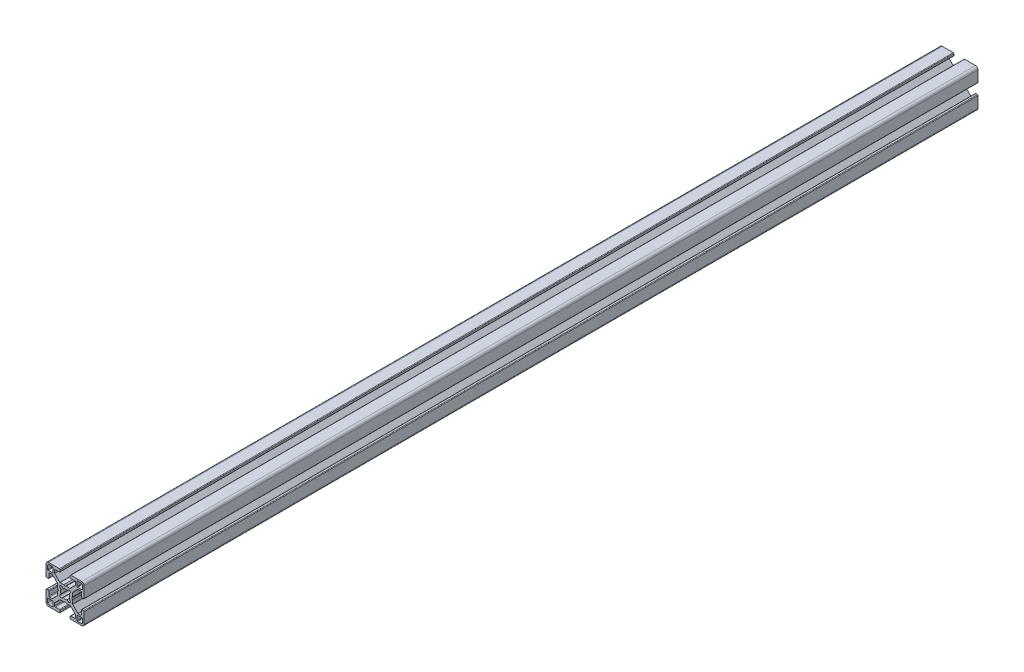
SolidWorks part; units mm, degrees
material "6105-T5 Aluminum"
ref_plane "Front Plane" through (0, 0, 0) normal (0, 0, 1) x (1, 0, 0)
ref_plane "Top Plane" through (0, 0, 0) normal (0, 1, 0) x (1, 0, 0)
ref_plane "Right Plane" through (0, 0, 0) normal (1, 0, 0) x (0, 0, -1)
sketch "Sketch1" plane through (0, 0, 0) normal (0, 0, 1) x (1, 0, 0)
  line L0 (9.5, -13.3189) -> (9.5, -9.88)
  line L1 (9.88, -9.5) -> (13.3189, -9.5)
  line L2 (13.6999, -9.881) -> (13.6999, -12.6999)
  line L3 (12.6999, -13.6999) -> (9.881, -13.6999)
  line L4 (-13.3189, -9.5) -> (-9.88, -9.5)
  line L5 (-9.5, -9.88) -> (-9.5, -13.3189)
  line L6 (-9.881, -13.6999) -> (-12.6999, -13.6999)
  line L7 (-13.6999, -12.6999) -> (-13.6999, -9.881)
  line L8 (-1.4942, -3.1981) -> (-2.4733, -3.9799)
  line L9 (-3.9799, -2.4733) -> (-3.1981, -1.4942)
  line L10 (-3.1981, 1.4942) -> (-3.9799, 2.4733)
  line L11 (-2.4733, 3.9799) -> (-1.4942, 3.1981)
  line L12 (1.4942, 3.1981) -> (2.4733, 3.9799)
  line L13 (3.9799, 2.4733) -> (3.1981, 1.4942)
  line L14 (3.1981, -1.4942) -> (3.9799, -2.4733)
  line L15 (2.4733, -3.9799) -> (1.4942, -3.1981)
  line L16 (-9.5, 13.3189) -> (-9.5, 9.88)
  line L17 (-9.88, 9.5) -> (-13.3189, 9.5)
  line L18 (-13.6999, 9.881) -> (-13.6999, 12.6999)
  line L19 (-12.6999, 13.6999) -> (-9.881, 13.6999)
  line L20 (9.881, 13.6999) -> (12.6999, 13.6999)
  line L21 (13.6999, 12.6999) -> (13.6999, 9.881)
  line L22 (13.3189, 9.5) -> (9.88, 9.5)
  line L23 (9.5, 9.88) -> (9.5, 13.3189)
  line L24 (12.7425, -4.5) -> (12.7425, -7.7325)
  line L25 (12.2428, -8.25) -> (10.2602, -8.25)
  line L26 (9.9066, -8.1035) -> (5.9811, -4.178)
  line L27 (5.8347, -3.8245) -> (5.8347, -1.0125)
  line L28 (5.8347, -1.0125) -> (5.3247, -0.0625)
  line L29 (5.3247, -0.0625) -> (5.8347, 0.8875)
  line L30 (5.8347, 0.8875) -> (5.8347, 3.8245)
  line L31 (5.9811, 4.178) -> (9.9066, 8.1035)
  line L32 (10.2602, 8.25) -> (12.2428, 8.25)
  line L33 (12.7425, 7.7325) -> (12.7425, 4.5)
  line L34 (13.2425, 4) -> (14.4999, 4)
  line L35 (14.9999, 4.5) -> (14.9999, 12.9999)
  line L36 (12.9999, 14.9999) -> (4.5, 14.9999)
  line L37 (4, 14.4999) -> (4, 13.2425)
  line L38 (4.5, 12.7425) -> (7.7325, 12.7425)
  line L39 (8.25, 12.2428) -> (8.25, 10.2602)
  line L40 (8.1035, 9.9066) -> (4.178, 5.9811)
  line L41 (3.8245, 5.8347) -> (0.95, 5.8347)
  line L42 (0.95, 5.8347) -> (0, 5.3247)
  line L43 (0, 5.3247) -> (-0.95, 5.8347)
  line L44 (-0.95, 5.8347) -> (-3.8245, 5.8347)
  line L45 (-4.178, 5.9811) -> (-8.1035, 9.9066)
  line L46 (-8.25, 10.2602) -> (-8.25, 12.2428)
  line L47 (-7.7325, 12.7425) -> (-4.5, 12.7425)
  line L48 (-4, 13.2425) -> (-4, 14.4999)
  line L49 (-4.5, 14.9999) -> (-12.9999, 14.9999)
  line L50 (-14.9999, 12.9999) -> (-14.9999, 4.5)
  line L51 (-14.4999, 4) -> (-13.2425, 4)
  line L52 (-12.7425, 4.5) -> (-12.7425, 7.7325)
  line L53 (-12.2428, 8.25) -> (-10.2602, 8.25)
  line L54 (-9.9066, 8.1035) -> (-5.9811, 4.178)
  line L55 (-5.8347, 3.8245) -> (-5.8347, 0.8875)
  line L56 (-5.8347, 0.8875) -> (-5.3247, -0.0625)
  line L57 (-5.3247, -0.0625) -> (-5.8347, -1.0125)
  line L58 (-5.8347, -1.0125) -> (-5.8347, -3.8245)
  line L59 (-5.9811, -4.178) -> (-9.9066, -8.1035)
  line L60 (-10.2602, -8.25) -> (-12.2428, -8.25)
  line L61 (-12.7425, -7.7325) -> (-12.7425, -4.5)
  line L62 (-13.2425, -4) -> (-14.4999, -4)
  line L63 (-14.9999, -4.5) -> (-14.9999, -12.9999)
  line L64 (-12.9999, -14.9999) -> (-4.5, -14.9999)
  line L65 (-4, -14.4999) -> (-4, -13.2425)
  line L66 (-4.5, -12.7425) -> (-7.7325, -12.7425)
  line L67 (-8.25, -12.2428) -> (-8.25, -10.2602)
  line L68 (-8.1035, -9.9066) -> (-4.178, -5.9811)
  line L69 (-3.8245, -5.8347) -> (-0.95, -5.8347)
  line L70 (-0.95, -5.8347) -> (0, -5.3247)
  line L71 (0, -5.3247) -> (0.95, -5.8347)
  line L72 (0.95, -5.8347) -> (3.8245, -5.8347)
  line L73 (4.178, -5.9811) -> (8.1035, -9.9066)
  line L74 (8.25, -10.2602) -> (8.25, -12.2428)
  line L75 (7.7325, -12.7425) -> (4.5, -12.7425)
  line L76 (4, -13.2425) -> (4, -14.4999)
  line L77 (4.5, -14.9999) -> (12.9999, -14.9999)
  line L78 (14.9999, -12.9999) -> (14.9999, -4.5)
  line L79 (14.4999, -4) -> (13.2425, -4)
  arc A0 (9.5, -13.3189) -> (9.881, -13.6999) centre (9.881, -13.3189) ccw
  arc A1 (9.88, -9.5) -> (9.5, -9.88) centre (9.88, -9.88) ccw
  arc A2 (13.6999, -9.881) -> (13.3189, -9.5) centre (13.3189, -9.881) ccw
  arc A3 (12.6999, -13.6999) -> (13.6999, -12.6999) centre (12.6999, -12.6999) ccw
  arc A4 (-13.3189, -9.5) -> (-13.6999, -9.881) centre (-13.3189, -9.881) ccw
  arc A5 (-9.5, -9.88) -> (-9.88, -9.5) centre (-9.88, -9.88) ccw
  arc A6 (-9.881, -13.6999) -> (-9.5, -13.3189) centre (-9.881, -13.3189) ccw
  arc A7 (-13.6999, -12.6999) -> (-12.6999, -13.6999) centre (-12.6999, -12.6999) ccw
  arc A8 (-1.4942, -3.1981) -> (1.4942, -3.1981) centre (0, 0) ccw
  arc A9 (-3.9799, -2.4733) -> (-2.4733, -3.9799) centre (-3.1422, -3.1422) ccw
  arc A10 (-3.1981, 1.4942) -> (-3.1981, -1.4942) centre (0, 0) ccw
  arc A11 (-2.4733, 3.9799) -> (-3.9799, 2.4733) centre (-3.1422, 3.1422) ccw
  arc A12 (1.4942, 3.1981) -> (-1.4942, 3.1981) centre (0, 0) ccw
  arc A13 (3.9799, 2.4733) -> (2.4733, 3.9799) centre (3.1422, 3.1422) ccw
  arc A14 (3.1981, -1.4942) -> (3.1981, 1.4942) centre (0, 0) ccw
  arc A15 (2.4733, -3.9799) -> (3.9799, -2.4733) centre (3.1422, -3.1422) ccw
  arc A16 (-9.5, 13.3189) -> (-9.881, 13.6999) centre (-9.881, 13.3189) ccw
  arc A17 (-9.88, 9.5) -> (-9.5, 9.88) centre (-9.88, 9.88) ccw
  arc A18 (-13.6999, 9.881) -> (-13.3189, 9.5) centre (-13.3189, 9.881) ccw
  arc A19 (-12.6999, 13.6999) -> (-13.6999, 12.6999) centre (-12.6999, 12.6999) ccw
  arc A20 (9.881, 13.6999) -> (9.5, 13.3189) centre (9.881, 13.3189) ccw
  arc A21 (13.6999, 12.6999) -> (12.6999, 13.6999) centre (12.6999, 12.6999) ccw
  arc A22 (13.3189, 9.5) -> (13.6999, 9.881) centre (13.3189, 9.881) ccw
  arc A23 (9.5, 9.88) -> (9.88, 9.5) centre (9.88, 9.88) ccw
  arc A24 (13.2425, -4) -> (12.7425, -4.5) centre (13.2425, -4.5) ccw
  arc A25 (12.2428, -8.25) -> (12.7425, -7.7325) centre (12.2428, -7.75) ccw
  arc A26 (9.9066, -8.1035) -> (10.2602, -8.25) centre (10.2602, -7.75) ccw
  arc A27 (5.8347, -3.8245) -> (5.9811, -4.178) centre (6.3347, -3.8245) ccw
  arc A28 (5.9811, 4.178) -> (5.8347, 3.8245) centre (6.3347, 3.8245) ccw
  arc A29 (10.2602, 8.25) -> (9.9066, 8.1035) centre (10.2602, 7.75) ccw
  arc A30 (12.7425, 7.7325) -> (12.2428, 8.25) centre (12.2428, 7.75) ccw
  arc A31 (12.7425, 4.5) -> (13.2425, 4) centre (13.2425, 4.5) ccw
  arc A32 (14.4999, 4) -> (14.9999, 4.5) centre (14.4999, 4.5) ccw
  arc A33 (14.9999, 12.9999) -> (12.9999, 14.9999) centre (12.9999, 12.9999) ccw
  arc A34 (4.5, 14.9999) -> (4, 14.4999) centre (4.5, 14.4999) ccw
  arc A35 (4, 13.2425) -> (4.5, 12.7425) centre (4.5, 13.2425) ccw
  arc A36 (8.25, 12.2428) -> (7.7325, 12.7425) centre (7.75, 12.2428) ccw
  arc A37 (8.1035, 9.9066) -> (8.25, 10.2602) centre (7.75, 10.2602) ccw
  arc A38 (3.8245, 5.8347) -> (4.178, 5.9811) centre (3.8245, 6.3347) ccw
  arc A39 (-4.178, 5.9811) -> (-3.8245, 5.8347) centre (-3.8245, 6.3347) ccw
  arc A40 (-8.25, 10.2602) -> (-8.1035, 9.9066) centre (-7.75, 10.2602) ccw
  arc A41 (-7.7325, 12.7425) -> (-8.25, 12.2428) centre (-7.75, 12.2428) ccw
  arc A42 (-4.5, 12.7425) -> (-4, 13.2425) centre (-4.5, 13.2425) ccw
  arc A43 (-4, 14.4999) -> (-4.5, 14.9999) centre (-4.5, 14.4999) ccw
  arc A44 (-12.9999, 14.9999) -> (-14.9999, 12.9999) centre (-12.9999, 12.9999) ccw
  arc A45 (-14.9999, 4.5) -> (-14.4999, 4) centre (-14.4999, 4.5) ccw
  arc A46 (-13.2425, 4) -> (-12.7425, 4.5) centre (-13.2425, 4.5) ccw
  arc A47 (-12.2428, 8.25) -> (-12.7425, 7.7325) centre (-12.2428, 7.75) ccw
  arc A48 (-9.9066, 8.1035) -> (-10.2602, 8.25) centre (-10.2602, 7.75) ccw
  arc A49 (-5.8347, 3.8245) -> (-5.9811, 4.178) centre (-6.3347, 3.8245) ccw
  arc A50 (-5.9811, -4.178) -> (-5.8347, -3.8245) centre (-6.3347, -3.8245) ccw
  arc A51 (-10.2602, -8.25) -> (-9.9066, -8.1035) centre (-10.2602, -7.75) ccw
  arc A52 (-12.7425, -7.7325) -> (-12.2428, -8.25) centre (-12.2428, -7.75) ccw
  arc A53 (-12.7425, -4.5) -> (-13.2425, -4) centre (-13.2425, -4.5) ccw
  arc A54 (-14.4999, -4) -> (-14.9999, -4.5) centre (-14.4999, -4.5) ccw
  arc A55 (-14.9999, -12.9999) -> (-12.9999, -14.9999) centre (-12.9999, -12.9999) ccw
  arc A56 (-4.5, -14.9999) -> (-4, -14.4999) centre (-4.5, -14.4999) ccw
  arc A57 (-4, -13.2425) -> (-4.5, -12.7425) centre (-4.5, -13.2425) ccw
  arc A58 (-8.25, -12.2428) -> (-7.7325, -12.7425) centre (-7.75, -12.2428) ccw
  arc A59 (-8.1035, -9.9066) -> (-8.25, -10.2602) centre (-7.75, -10.2602) ccw
  arc A60 (-3.8245, -5.8347) -> (-4.178, -5.9811) centre (-3.8245, -6.3347) ccw
  arc A61 (4.178, -5.9811) -> (3.8245, -5.8347) centre (3.8245, -6.3347) ccw
  arc A62 (8.25, -10.2602) -> (8.1035, -9.9066) centre (7.75, -10.2602) ccw
  arc A63 (7.7325, -12.7425) -> (8.25, -12.2428) centre (7.75, -12.2428) ccw
  arc A64 (4.5, -12.7425) -> (4, -13.2425) centre (4.5, -13.2425) ccw
  arc A65 (4, -14.4999) -> (4.5, -14.9999) centre (4.5, -14.4999) ccw
  arc A66 (12.9999, -14.9999) -> (14.9999, -12.9999) centre (12.9999, -12.9999) ccw
  arc A67 (14.9999, -4.5) -> (14.4999, -4) centre (14.4999, -4.5) ccw
extrude "Extrude1" add sketch "Sketch1" against normal blind 702
